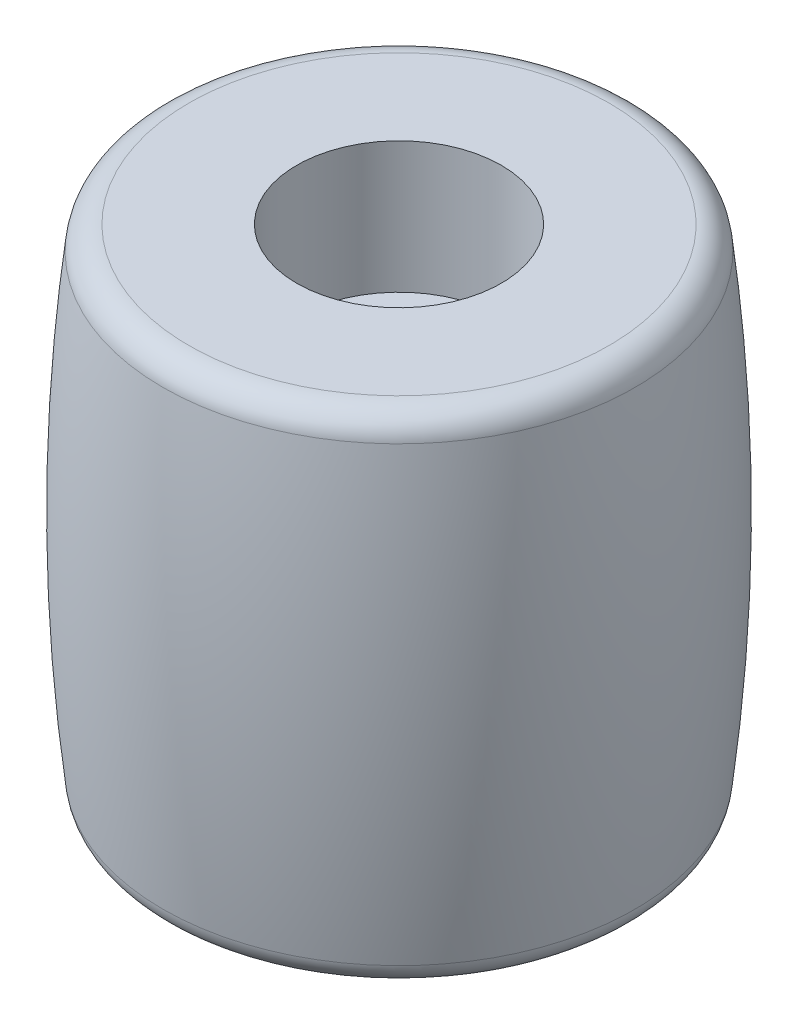
SolidWorks part; units mm, degrees
ref_plane "前视基准面" through (0, 0, 0) normal (0, 0, 1) x (1, 0, 0)
ref_plane "上视基准面" through (0, 0, 0) normal (0, 1, 0) x (1, 0, 0)
ref_plane "右视基准面" through (0, 0, 0) normal (1, 0, 0) x (0, 0, -1)
sketch "草图1" plane through (0, 0, 0) normal (0, 0, 1) x (1, 0, 0)
  line L0 (-2.5, 4.5) -> (-2.5, -4.5)
  line L1 (-2.5, -4.5) -> (-3.9, -4.5)
  line L2 (-3.9, -4.5) -> (-3.9, -9.5)
  line L3 (-3.9, -9.5) -> (-8.8959, -9.5)
  line L4 (-2.5, 4.5) -> (-3.9, 4.5)
  line L5 (-3.9, 4.5) -> (-3.9, 9.5)
  line L6 (-3.9, 9.5) -> (-8.8959, 9.5)
  line L7 (-2.5, 0) -> (0, 0) construction
  line L8 (0, 0) -> (0, 5.7115) construction
  line L9 (65.5, 0) -> (-9.5, 0) construction
  circle A0 centre (65.5, 0) radius 75
  point P5 (-2.5, 0)
  dimension "D2" = 150
  dimension "D6" = 9.5
  dimension "D1" = 19
  dimension "D3" = 2.5
  dimension "D4" = 3.9
  dimension "D5" = 5
revolve "旋转1" add sketch "草图1" angle 360 about L8
fillet "圆角1" radius 1 2 edges at (0, -9.5, -8.8959) (0, 9.5, -8.8959)
